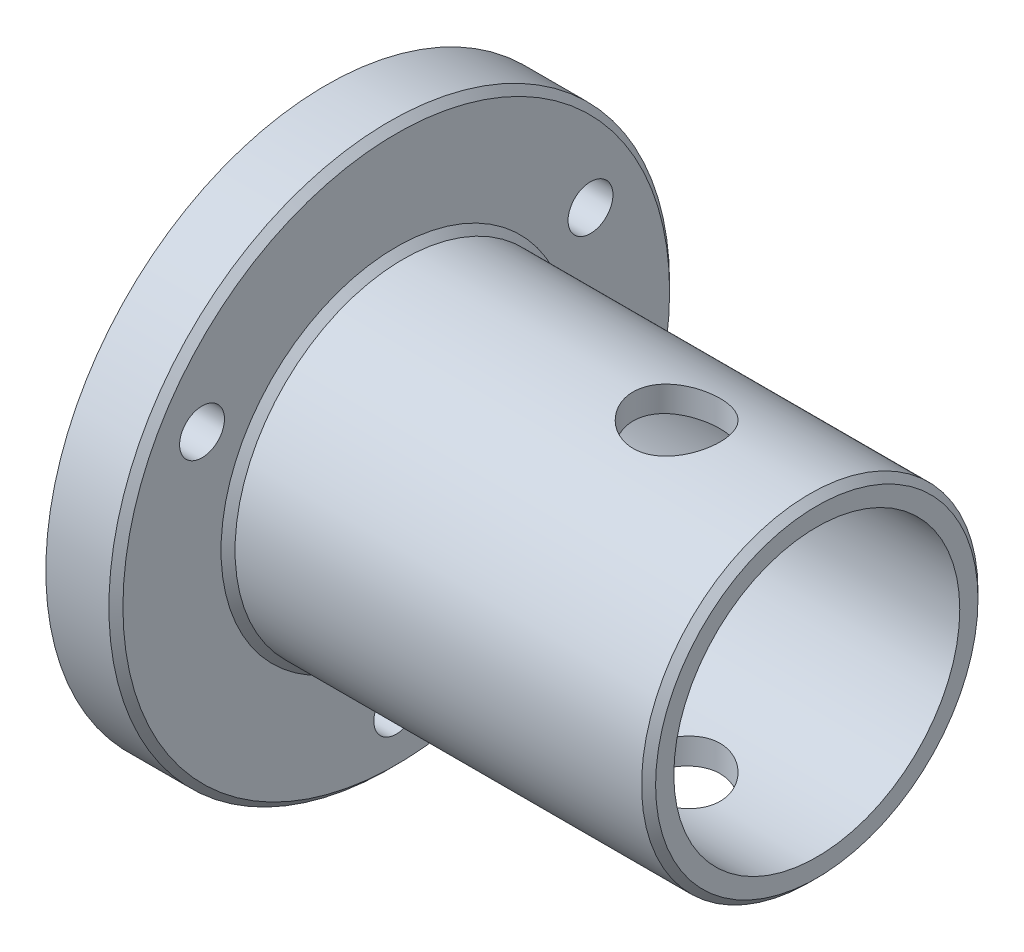
SolidWorks part; units mm, degrees
ref_plane "Front" through (0, 0, 0) normal (0, 0, 1) x (1, 0, 0)
ref_plane "Top" through (0, 0, 0) normal (0, 1, 0) x (1, 0, 0)
ref_plane "Right" through (0, 0, 0) normal (1, 0, 0) x (0, 0, -1)
sketch "草图1" plane through (0, 0, 0) normal (1, 0, 0) x (0, 0, -1)
  line L0 (0, 0) -> (0, -16) construction
  line L1 (0, 0) -> (13.8564, 8) construction
  line L2 (0, 0) -> (-13.8564, 8) construction
  circle A0 centre (0, 0) radius 10
  circle A1 centre (0, 0) radius 20
  circle A2 centre (0, 0) radius 16 construction
  circle A3 centre (0, 0) radius 12
  circle A4 centre (-13.8564, 8) radius 1.6
  circle A5 centre (13.8564, 8) radius 1.6
  circle A6 centre (0, -16) radius 1.6
extrude "凸台-拉伸1" add sketch "草图1" along normal blind 5 contours A1
sketch "草图6" plane through (5, 0, 0) normal (1, 0, 0) x (0, 0, -1)
  circle A0 centre (0, 0) radius 10
  circle A1 centre (0, 0) radius 12
extrude "凸台-拉伸2" add sketch "草图6" along normal blind 30 contours A1
sketch "草图7" plane through (35, 0, 0) normal (1, 0, 0) x (0, 0, -1)
  circle A0 centre (0, 0) radius 10.2
extrude "切除-拉伸2" cut sketch "草图7" against normal blind 30
chamfer "倒角1" distance 0.5 angle 45 1 edges at (35, 0, -12)
sketch "草图8" plane through (0, 0, 0) normal (0, 1, 0) x (1, 0, 0)
  line L0 (5, 0) -> (25, 0) construction
  line L1 (5, -20) -> (5, 20) construction
  circle A0 centre (25, 0) radius 3.1
extrude "切除-拉伸3" cut sketch "草图8" along normal through all both and the other way through all
chamfer "倒角2" distance 0.5 angle 45 1 edges at (5, 0, -20)
chamfer "倒角3" distance 0.5 angle 45 1 edges at (5, 0, -12)
sketch "草图9" plane through (0, 0, 0) normal (-1, 0, 0) x (0, 0, 1)
  circle A0 centre (-13.8564, 8) radius 1.6
  circle A1 centre (13.8564, 8) radius 1.6
  circle A2 centre (0, -16) radius 1.6
extrude "切除-拉伸4" cut sketch "草图9" against normal blind 10
